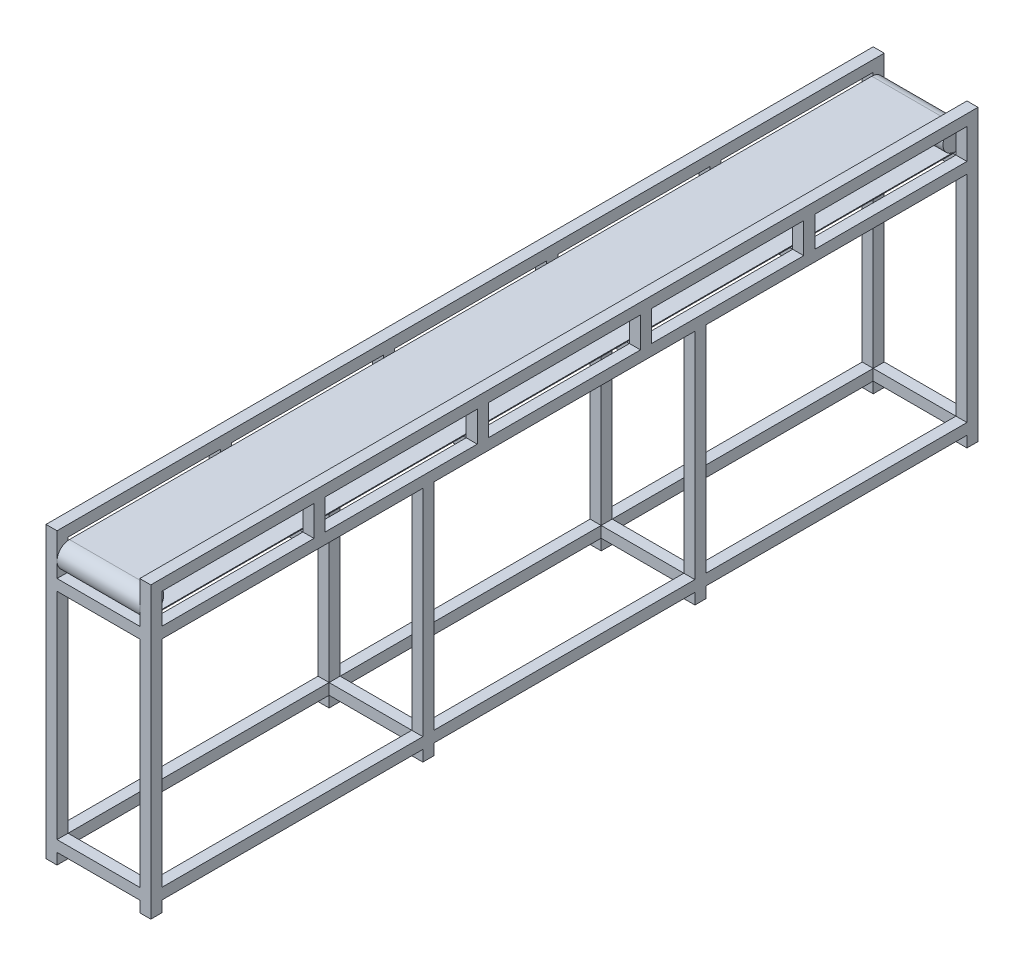
SolidWorks part; units mm, degrees
other "Band"
other "Rahmen"
ref_plane "Ebene vorne" through (0, 0, 0) normal (0, 0, 1) x (1, 0, 0)
ref_plane "Ebene oben" through (0, 0, 0) normal (0, 1, 0) x (1, 0, 0)
ref_plane "Ebene rechts" through (0, 0, 0) normal (1, 0, 0) x (0, 0, -1)
sketch "Skizze1" plane through (0, 0, 0) normal (0, 0, 1) x (1, 0, 0)
  line L0 (0, 880) -> (0, 0) construction
  line L1 (-190, 1050) -> (-150, 1050)
  line L2 (-190, 1050) -> (-190, 900)
  line L3 (-190, 900) -> (-150, 900)
  line L4 (-150, 1050) -> (-150, 900)
  line L5 (-190, 1050) -> (-150, 900) construction
  line L6 (-190, 900) -> (-150, 1050) construction
  line L7 (150, 1050) -> (190, 1050)
  line L8 (150, 1050) -> (150, 900)
  line L9 (150, 900) -> (190, 900)
  line L10 (190, 1050) -> (190, 900)
  line L11 (150, 1050) -> (190, 900) construction
  line L12 (150, 900) -> (190, 1050) construction
  line L13 (-190, 900) -> (190, 900)
  line L14 (-190, 900) -> (-190, 860)
  line L15 (-190, 860) -> (190, 860)
  line L16 (190, 900) -> (190, 860)
  line L17 (-190, 900) -> (190, 860) construction
  line L18 (-190, 860) -> (190, 900) construction
  line L20 (-190, 860) -> (-150, 860)
  line L21 (-190, 860) -> (-190, 0)
  line L22 (-190, 0) -> (-150, 0)
  line L23 (-150, 860) -> (-150, 0)
  line L24 (-190, 860) -> (-150, 0) construction
  line L25 (-190, 0) -> (-150, 860) construction
  line L26 (190, 860) -> (150, 860)
  line L27 (190, 860) -> (190, 0)
  line L28 (190, 0) -> (150, 0)
  line L29 (150, 860) -> (150, 0)
  line L30 (190, 860) -> (150, 0) construction
  line L31 (190, 0) -> (150, 860) construction
  point P0 (-170, 975)
  point P5 (170, 975)
  point P10 (0, 880)
  point P21 (-170, 430)
  point P25 (170, 430)
  dimension "D1" = 300
  dimension "D2" = 40
  dimension "D3" = 40
  dimension "D4" = 900
  dimension "D5" = 150
  dimension "D6" = 40
  dimension "D7" = 40
extrude "Aufsatz-Linear austragen1" add sketch "Skizze1" against normal blind 3000 contours L15 L29 L28 L27 | L16 L9 L13 L3 L14 L15 | L10 L7 L8 L9 | L4 L1 L2 L3 | L23 L15 L21 L22
sketch "Skizze2" plane through (190, 0, 0) normal (1, 0, 0) x (0, 0, -1)
  line L0 (3000, 860) -> (0, 860) construction
  line L1 (3000, 900) -> (0, 900) construction
  line L2 (3000, 860) -> (0, 860) construction
  line L3 (3000, 900) -> (0, 900) construction
  line L10 (40, 900) -> (592, 900)
  line L11 (3000, 0) -> (0, 0) construction
  line L16 (40, 900) -> (40, 1010)
  line L17 (40, 1010) -> (592, 1010)
  line L22 (592, 900) -> (592, 1010)
  line L23 (40, 900) -> (592, 1010) construction
  line L28 (40, 1010) -> (592, 900) construction
  line L29 (632, 900) -> (1184, 900)
  line L34 (632, 900) -> (632, 1010)
  line L35 (632, 1010) -> (1184, 1010)
  line L36 (40, 860) -> (986.6667, 860)
  line L37 (40, 860) -> (40, 80)
  line L38 (40, 80) -> (986.6667, 80)
  line L39 (986.6667, 860) -> (986.6667, 80)
  line L40 (40, 860) -> (986.6667, 80) construction
  line L41 (40, 80) -> (986.6667, 860) construction
  line L42 (1026.6667, 860) -> (1973.3333, 860)
  line L43 (1026.6667, 860) -> (1026.6667, 80)
  line L44 (1026.6667, 80) -> (1973.3333, 80)
  line L45 (1973.3333, 860) -> (1973.3333, 80)
  line L46 (1026.6667, 860) -> (1973.3333, 80) construction
  line L47 (1026.6667, 80) -> (1973.3333, 860) construction
  line L48 (2013.3333, 860) -> (2960, 860)
  line L49 (2013.3333, 860) -> (2013.3333, 80)
  line L50 (2013.3333, 80) -> (2960, 80)
  line L51 (2960, 860) -> (2960, 80)
  line L52 (2013.3333, 860) -> (2960, 80) construction
  line L53 (2013.3333, 80) -> (2960, 860) construction
  line L54 (40, 0) -> (986.6667, 0)
  line L55 (40, 0) -> (40, 40)
  line L56 (40, 40) -> (986.6667, 40)
  line L57 (986.6667, 0) -> (986.6667, 40)
  line L58 (40, 0) -> (986.6667, 40) construction
  line L59 (40, 40) -> (986.6667, 0) construction
  line L61 (1026.6667, 0) -> (1973.3333, 0)
  line L62 (1026.6667, 0) -> (1026.6667, 40)
  line L63 (1026.6667, 40) -> (1973.3333, 40)
  line L64 (1973.3333, 0) -> (1973.3333, 40)
  line L65 (1026.6667, 0) -> (1973.3333, 40) construction
  line L66 (1026.6667, 40) -> (1973.3333, 0) construction
  line L67 (2013.3333, 0) -> (2960, 0)
  line L68 (2013.3333, 0) -> (2013.3333, 40)
  line L69 (2013.3333, 40) -> (2960, 40)
  line L70 (2960, 0) -> (2960, 40)
  line L71 (2013.3333, 0) -> (2960, 40) construction
  line L72 (2013.3333, 40) -> (2960, 0) construction
  line L73 (1184, 900) -> (1184, 1010)
  line L74 (632, 900) -> (1184, 1010) construction
  line L75 (632, 1010) -> (1184, 900) construction
  line L76 (1224, 900) -> (1776, 900)
  line L77 (1224, 900) -> (1224, 1010)
  line L78 (1224, 1010) -> (1776, 1010)
  line L79 (1776, 900) -> (1776, 1010)
  line L80 (1224, 900) -> (1776, 1010) construction
  line L81 (1224, 1010) -> (1776, 900) construction
  line L82 (1816, 900) -> (2368, 900)
  line L83 (1816, 900) -> (1816, 1010)
  line L84 (1816, 1010) -> (2368, 1010)
  line L85 (2368, 900) -> (2368, 1010)
  line L86 (1816, 900) -> (2368, 1010) construction
  line L87 (1816, 1010) -> (2368, 900) construction
  line L88 (2408, 900) -> (2960, 900)
  line L89 (2408, 900) -> (2408, 1010)
  line L90 (2408, 1010) -> (2960, 1010)
  line L91 (2960, 900) -> (2960, 1010)
  line L92 (2408, 900) -> (2960, 1010) construction
  line L93 (2408, 1010) -> (2960, 900) construction
  line L94 (0, 1050) -> (0, 0) construction
  line L95 (3000, 1050) -> (0, 1050) construction
  line L96 (3000, 1050) -> (3000, 0) construction
  point P8 (316, 955)
  point P13 (908, 955)
  point P18 (1500, 955)
  point P23 (2092, 955)
  point P28 (2684, 955)
  point P35 (513.3333, 470)
  point P40 (1500, 470)
  point P45 (2486.6667, 470)
  point P50 (513.3333, 20)
  point P57 (1500, 20)
  point P62 (2486.6667, 20)
  dimension "D1" = 40
  dimension "D2" = 40
  dimension "D3" = 40
  dimension "D4" = 40
  dimension "D5" = 40
  dimension "D6" = 40
  dimension "D7" = 40
  dimension "D8" = 40
  dimension "D9" = 40
  dimension "D10" = 40
  dimension "D11" = 40
extrude "Schnitt-Linear austragen1" cut sketch "Skizze2" against normal through all and the other way through all
sketch "Skizze3" plane through (0, 900, 0) normal (0, 1, 0) x (1, 0, 0)
  line L1 (-150, 2960) -> (150, 2960)
  line L2 (-150, 2960) -> (-150, 2408)
  line L3 (-150, 2408) -> (150, 2408)
  line L4 (150, 2960) -> (150, 2408)
  line L5 (-150, 2960) -> (150, 2408) construction
  line L6 (-150, 2408) -> (150, 2960) construction
  line L7 (150, 2368) -> (-150, 2368)
  line L8 (150, 2368) -> (150, 1816)
  line L9 (150, 1816) -> (-150, 1816)
  line L10 (-150, 2368) -> (-150, 1816)
  line L11 (150, 2368) -> (-150, 1816) construction
  line L12 (150, 1816) -> (-150, 2368) construction
  line L13 (-150, 1776) -> (150, 1776)
  line L14 (-150, 1776) -> (-150, 1224)
  line L15 (-150, 1224) -> (150, 1224)
  line L16 (150, 1776) -> (150, 1224)
  line L17 (-150, 1776) -> (150, 1224) construction
  line L18 (-150, 1224) -> (150, 1776) construction
  line L19 (150, 1184) -> (-150, 1184)
  line L20 (150, 1184) -> (150, 632)
  line L21 (150, 632) -> (-150, 632)
  line L22 (-150, 1184) -> (-150, 632)
  line L23 (150, 1184) -> (-150, 632) construction
  line L24 (150, 632) -> (-150, 1184) construction
  line L25 (-150, 592) -> (150, 592)
  line L26 (-150, 592) -> (-150, 40)
  line L27 (-150, 40) -> (150, 40)
  line L28 (150, 592) -> (150, 40)
  line L29 (-150, 592) -> (150, 40) construction
  line L30 (-150, 40) -> (150, 592) construction
  point P4 (0, 2684)
  point P11 (0, 2092)
  point P18 (0, 1500)
  point P25 (0, 908)
  point P32 (0, 316)
extrude "Schnitt-Linear austragen2" cut sketch "Skizze3" against normal through all
sketch "Skizze4" plane through (150, 0, 0) normal (-1, 0, 0) x (0, 0, 1)
  line L0 (-2955, 955) -> (-45, 955) construction
  line L1 (-2955, 997) -> (-45, 997)
  line L2 (-2955, 913) -> (-45, 913)
  line L3 (-2955, 1000) -> (-45, 1000)
  line L4 (-2955, 910) -> (-45, 910)
  line L5 (-3000, 1050) -> (0, 1050) construction
  line L6 (-2408, 900) -> (-2960, 900) construction
  line L7 (0, 1050) -> (0, 900) construction
  line L8 (-3000, 1050) -> (-3000, 900) construction
  line L9 (0, 1050) -> (0, 900) construction
  line L10 (-3000, 1050) -> (-3000, 900) construction
  arc A0 (-2955, 997) -> (-2955, 913) centre (-2955, 955) ccw
  arc A1 (-45, 913) -> (-45, 997) centre (-45, 955) ccw
  arc A2 (-45, 910) -> (-45, 1000) centre (-45, 955) ccw
  arc A3 (-2955, 1000) -> (-2955, 910) centre (-2955, 955) ccw
  point P2 (-1500, 955)
  dimension "D2" = 50
  dimension "D3" = 10
  dimension "D1" = 3
extrude "Aufsatz-Linear austragen2" add sketch "Skizze4" along normal up to surface (300 mm away) separate body up to face at (-150, 958.3333, -1500)
sketch "Skizze5" plane through (150, 0, 0) normal (-1, 0, 0) x (0, 0, 1)
  line L0 (-2955, 913) -> (-45, 913) construction
  line L1 (-45, 997) -> (-2955, 997) construction
  line L2 (-2955, 913) -> (-45, 913) construction
  line L3 (-45, 997) -> (-2955, 997) construction
  line L5 (-2925, 997) -> (-75, 997)
  line L6 (-2925, 997) -> (-2925, 992)
  line L7 (-2925, 992) -> (-75, 992)
  line L8 (-75, 997) -> (-75, 992)
  line L9 (-2925, 997) -> (-75, 992) construction
  line L10 (-2925, 992) -> (-75, 997) construction
  arc A0 (-45, 913) -> (-45, 997) centre (-45, 955) ccw construction
  arc A1 (-2955, 997) -> (-2955, 913) centre (-2955, 955) ccw construction
  arc A2 (-45, 913) -> (-45, 997) centre (-45, 955) ccw construction
  arc A3 (-2955, 997) -> (-2955, 913) centre (-2955, 955) ccw construction
  circle A4 centre (-2955, 955) radius 42
  circle A5 centre (-45, 955) radius 42
  point P12 (-1500, 994.5)
  line M3 (-632, 1010) -> (-632, 900)
  line M5 (-592, 900) -> (-592, 1010)
  line M7 (-40, 1010) -> (-40, 900)
  line M13 (-2960, 900) -> (-2960, 1010)
  line M15 (-2408, 1010) -> (-2408, 900)
  line M17 (-2368, 900) -> (-2368, 1010)
  line M19 (-1816, 1010) -> (-1816, 900)
  line M21 (-1776, 900) -> (-1776, 1010)
  line M23 (-1224, 1010) -> (-1224, 900)
  line M25 (-1184, 900) -> (-1184, 1010)
  dimension "D1" = 5
  dimension "D2" = 30
  dimension "D3" = 30
extrude "Aufsatz-Linear austragen3" add sketch "Skizze5" along normal up to surface (300 mm away) contours L6 L7 L5 M15 | A4 M13 | A4 M13 | L7 L5 M17 M19 | L7 L5 M15 M17 | L7 L5 M21 M23 | L7 L5 M19 M21 | L7 L5 M25 M3 | L7 L5 M23 M25 | L7 L5 M3 M5 | A5 M7 | A5 M7 | L8 L5 L7 M5 up to face at (-150, 958.3333, -1500)
sketch "Skizze6" plane through (150, 0, 0) normal (-1, 0, 0) x (0, 0, 1)
  line L0 (-3000, 860) -> (-3000, 0) construction
  line L1 (-2960, 80) -> (-3000, 80)
  line L2 (-2960, 80) -> (-2960, 40)
  line L3 (-2960, 40) -> (-3000, 40)
  line L4 (-3000, 80) -> (-3000, 40)
  line L5 (-2960, 80) -> (-3000, 40) construction
  line L6 (-2960, 40) -> (-3000, 80) construction
  line L7 (0, 860) -> (0, 0) construction
  line L8 (-1973.3333, 40) -> (-2013.3333, 40)
  line L9 (-1973.3333, 40) -> (-1973.3333, 80)
  line L10 (-1973.3333, 80) -> (-2013.3333, 80)
  line L11 (-2013.3333, 40) -> (-2013.3333, 80)
  line L12 (-1973.3333, 40) -> (-2013.3333, 80) construction
  line L13 (-1973.3333, 80) -> (-2013.3333, 40) construction
  line L14 (-40, 80) -> (0, 80)
  line L15 (-40, 80) -> (-40, 40)
  line L16 (-40, 40) -> (0, 40)
  line L17 (0, 80) -> (0, 40)
  line L18 (-40, 80) -> (0, 40) construction
  line L19 (-40, 40) -> (0, 80) construction
  line L21 (-986.6667, 80) -> (-1026.6667, 80)
  line L22 (-986.6667, 80) -> (-986.6667, 40)
  line L23 (-986.6667, 40) -> (-1026.6667, 40)
  line L24 (-1026.6667, 80) -> (-1026.6667, 40)
  line L25 (-986.6667, 80) -> (-1026.6667, 40) construction
  line L26 (-986.6667, 40) -> (-1026.6667, 80) construction
  point P4 (-2980, 60)
  point P12 (-1993.3333, 60)
  point P19 (-20, 60)
  point P27 (-1006.6667, 60)
  point P30 (0, 0)
extrude "Aufsatz-Linear austragen4" add sketch "Skizze6" along normal up to surface (300 mm away) up to face at (-150, 955, -1500)
